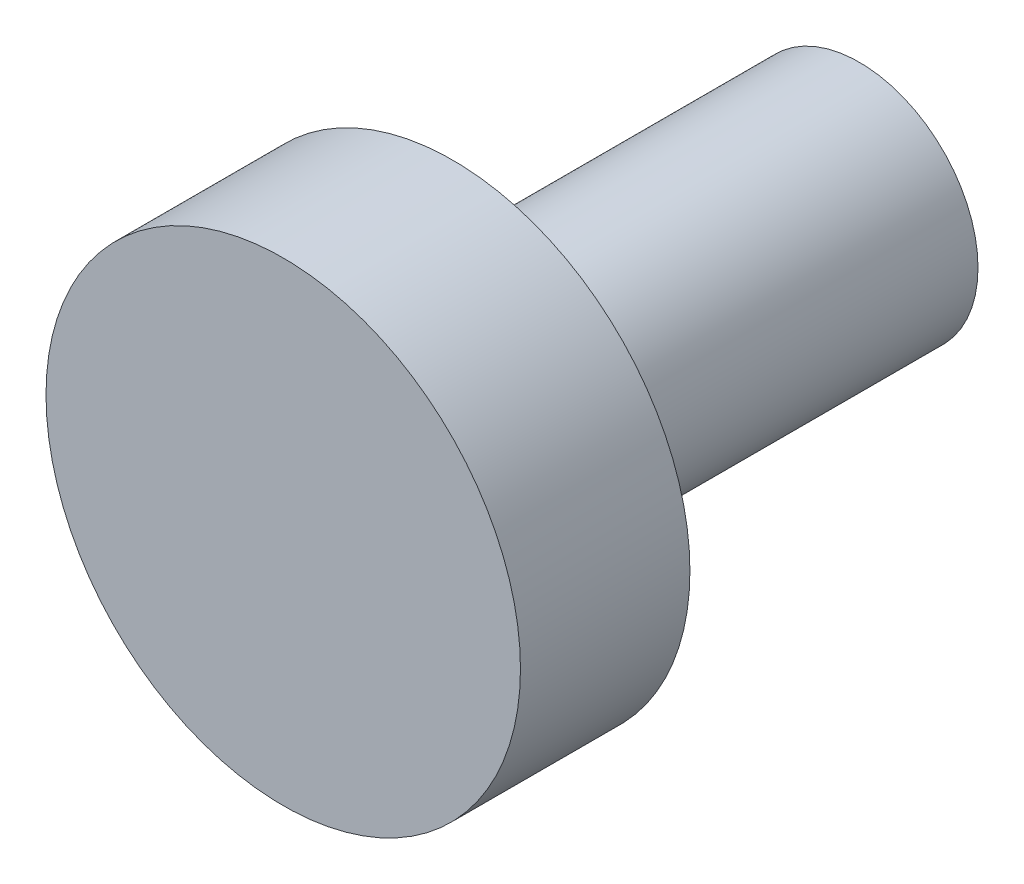
SolidWorks part; units mm, degrees
ref_plane "Front" through (0, 0, 0) normal (0, 0, 1) x (1, 0, 0)
ref_plane "Top" through (0, 0, 0) normal (0, 1, 0) x (1, 0, 0)
ref_plane "Right" through (0, 0, 0) normal (1, 0, 0) x (0, 0, -1)
sketch "Sketch1" plane through (0, 0, 0) normal (0, 0, 1) x (1, 0, 0)
  circle A0 centre (0, 0) radius 1.75
  dimension "D1" = 3.5
extrude "Boss-Extrude1" add sketch "Sketch1" along normal blind 6
sketch "Sketch2" plane through (0, 0, 6) normal (0, 0, 1) x (1, 0, 0)
  circle A0 centre (0, 0) radius 3.5
  dimension "D1" = 7
extrude "Boss-Extrude2" add sketch "Sketch2" along normal blind 2.5
